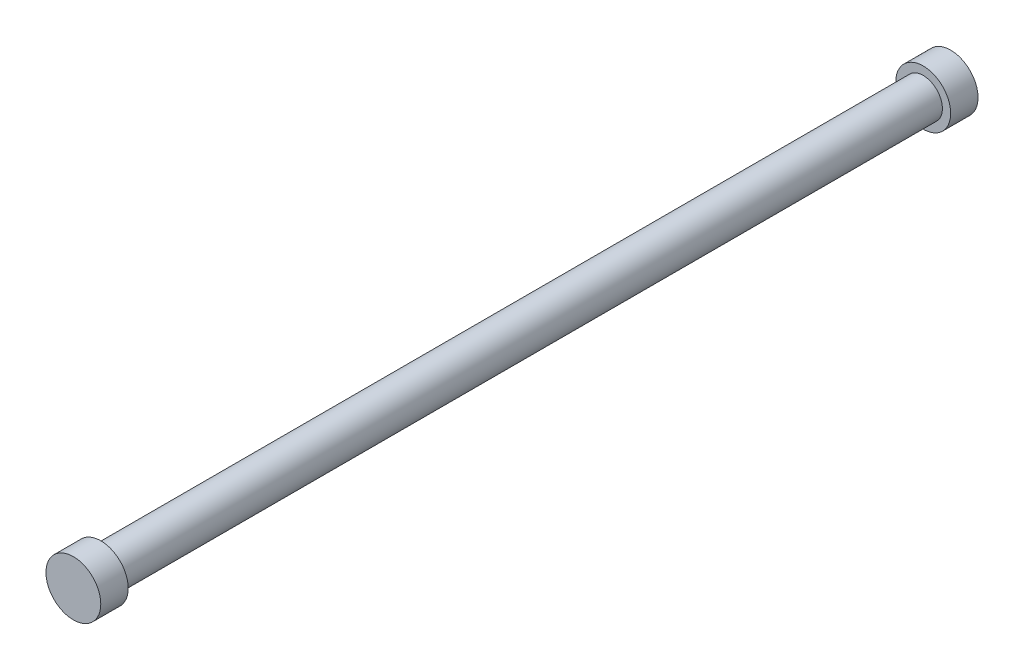
SolidWorks part; units mm, degrees
material "ASTM A36 Steel"
ref_plane "Front Plane" through (0, 0, 0) normal (0, 0, 1) x (1, 0, 0)
ref_plane "Top Plane" through (0, 0, 0) normal (0, 1, 0) x (1, 0, 0)
ref_plane "Right Plane" through (0, 0, 0) normal (1, 0, 0) x (0, 0, -1)
sketch "Sketch1" plane through (0, 0, 0) normal (0, 0, 1) x (1, 0, 0)
  circle A0 centre (0, 0) radius 7
  dimension "D1" = 14
extrude "Boss-Extrude1" add sketch "Sketch1" along normal blind 320
sketch "Sketch2" plane through (0, 0, 320) normal (0, 0, 1) x (1, 0, 0)
  circle A0 centre (0, 0) radius 10
  dimension "D1" = 20
extrude "Boss-Extrude2" add sketch "Sketch2" against normal blind 10
sketch "Sketch3" plane through (0, 0, 0) normal (0, 0, -1) x (-1, 0, 0)
  circle A0 centre (0, 0) radius 10
  dimension "D1" = 20
extrude "Boss-Extrude3" add sketch "Sketch3" against normal blind 10
